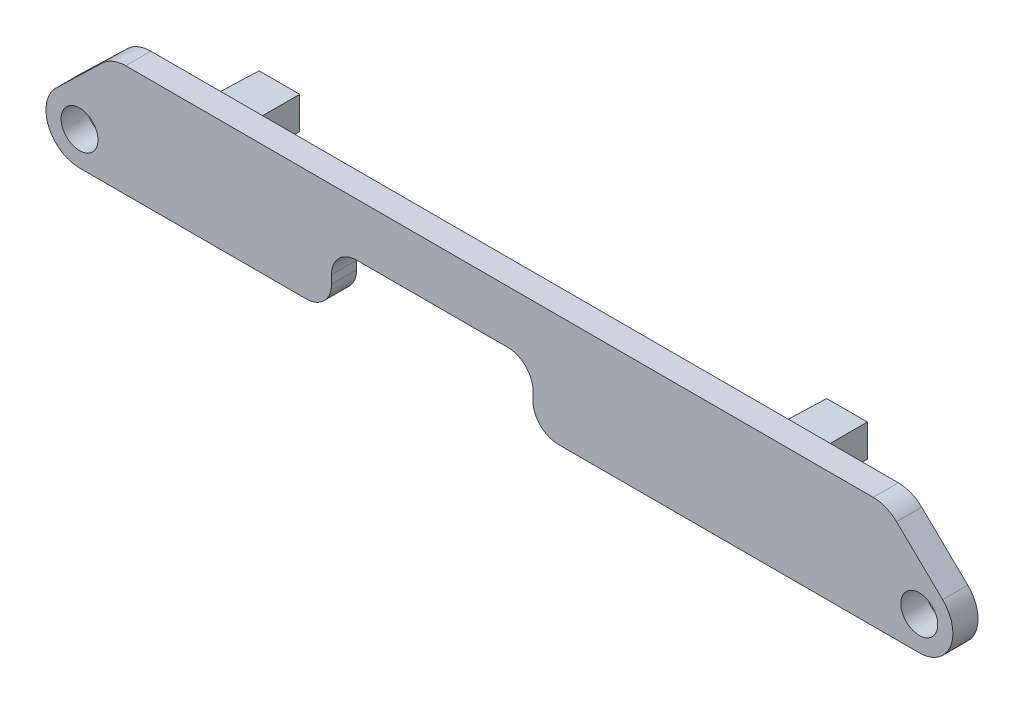
SolidWorks part; units mm, degrees
ref_plane "前视基准面" through (0, 0, 0) normal (0, 0, 1) x (1, 0, 0)
ref_plane "上视基准面" through (0, 0, 0) normal (0, 1, 0) x (1, 0, 0)
ref_plane "右视基准面" through (0, 0, 0) normal (1, 0, 0) x (0, 0, -1)
sketch "草图1" plane through (0, 0, 0) normal (0, 0, 1) x (1, 0, 0)
  line L0 (0, 0) -> (0, -8.4084) construction
  line L1 (-25, -3.5) -> (25, -3.5)
  line L2 (23.0639, 3.15) -> (-23.0639, 3.15)
  line L3 (-26.3893, -0.0613) -> (-23.0639, 3.15)
  line L4 (26.3893, -0.0613) -> (23.0639, 3.15)
  arc A0 (-26.3893, -0.0613) -> (-25, -3.5) centre (-25, -1.5) ccw
  arc A1 (-25, -3.5) -> (-26.3893, -0.0613) centre (-25, -1.5) ccw construction
  arc A2 (25, -3.5) -> (26.3893, -0.0613) centre (25, -1.5) cw construction
  arc A3 (26.3893, -0.0613) -> (25, -3.5) centre (25, -1.5) cw
  point P4 (0, -3.5)
  point P10 (0, 0)
  point P11 (0, 0)
  point P15 (0, 3.15)
  dimension "D1" = 4
  dimension "D3" = 1.5
  dimension "D2" = 25
  dimension "D4" = 44
  dimension "D5" = 6.65
extrude "凸台-拉伸1" add sketch "草图1" against normal blind 1.5
fillet "圆角1" radius 2 2 edges at (23.0639, 3.15, -0.75) (-23.0639, 3.15, -0.75)
sketch "草图2" plane through (0, 0, 0) normal (0, 0, 1) x (1, 0, 0)
  line L0 (-25, -3.5) -> (25, -3.5) construction
  line L1 (2, -3.5) -> (-10, -3.5)
  line L2 (2, -3.5) -> (2, 0)
  line L3 (2, 0) -> (-10, 0)
  line L4 (-10, -3.5) -> (-10, 0)
  point P6 (0, 0)
  dimension "D1" = 2
  dimension "D2" = 10
  dimension "D3" = 3.5
extrude "切除-拉伸1" cut sketch "草图2" against normal blind 1.5
sketch "草图3" plane through (0, 0, -1.5) normal (0, 0, -1) x (-1, 0, 0)
  line L1 (18.15, 1.1) -> (15.65, 1.1)
  line L2 (18.15, 1.1) -> (18.15, 3.1)
  line L3 (18.15, 3.1) -> (15.65, 3.1)
  line L4 (15.65, 1.1) -> (15.65, 3.1)
  point P4 (0, 0)
  dimension "D1" = 15.65
  dimension "D2" = 3.1
  dimension "D3" = 2.5
  dimension "D4" = 2
extrude "凸台-拉伸2" add sketch "草图3" along normal blind 2.3 draft 1
hole_wizard "M2 间隙孔1" positions "草图4" profile "草图6" hole size "M2" standard "GB" end condition through all
sketch "草图4" plane through (0, 0, -1.5) normal (0, 0, -1) x (-1, 0, 0)
  line L0 (0, 0) -> (25, -1.5)
  line L1 (-2, 0) -> (10, 0) construction
  point P0 (25, -1.5)
  dimension "D1" = 25
  dimension "D2" = 1.5
sketch "草图6" plane through (-25, -1.5, -1.5) normal (1, 0, 0) x (0, 1, 0)
  line L0 (0, 0) -> (0, 1.5)
  line L1 (0, 1.5) -> (1.1, 1.5)
  line L2 (1.1, 1.5) -> (1.1, 0)
  line L5 (1.1, 0) -> (0, 0)
  line L11 (0, -6.35) -> (0, 107.95) construction
  dimension "通孔孔直径" = 2.2
  dimension "通孔孔深度" = 1.5
mirror "镜向1" about plane through (0, 0, 0) normal (1, 0, 0) of "M2 间隙孔1", "凸台-拉伸2"
fillet "圆角2" radius 1.5 4 edges at (2, -3.5, -0.75) (-10, -3.5, -0.75) (2, 0, -0.75) (-10, 0, -0.75)
